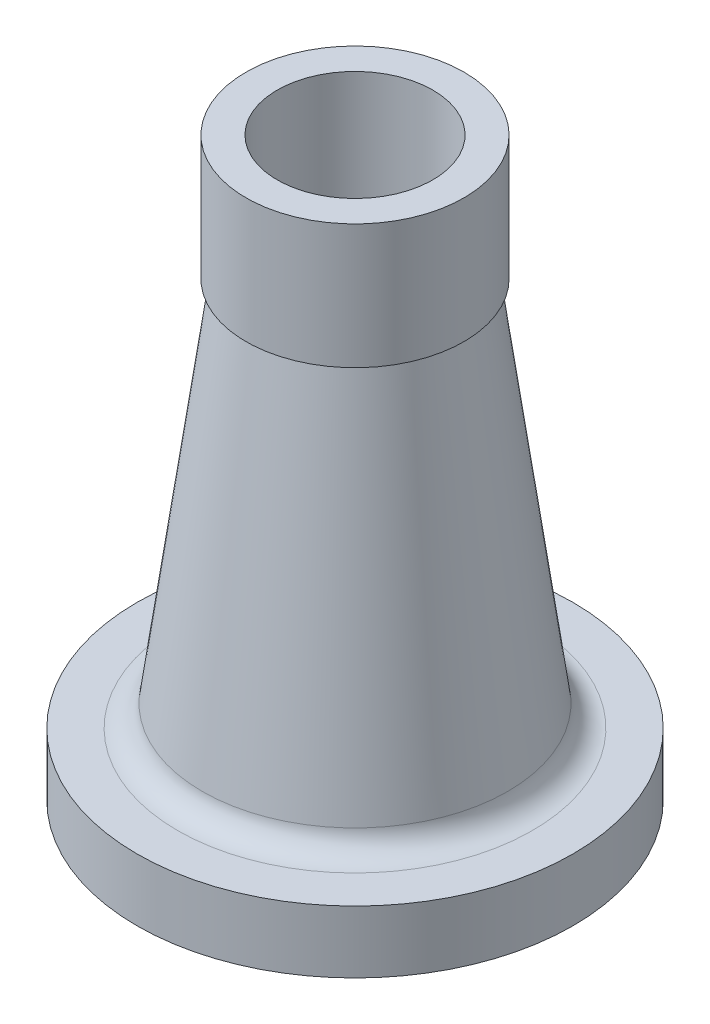
SolidWorks part; units mm, degrees
material "Gray Cast Iron"
ref_plane "Front Plane" through (0, 0, 0) normal (0, 0, 1) x (1, 0, 0)
ref_plane "Top Plane" through (0, 0, 0) normal (0, 1, 0) x (1, 0, 0)
ref_plane "Right Plane" through (0, 0, 0) normal (1, 0, 0) x (0, 0, -1)
sketch "Sketch1" plane through (0, 0, 0) normal (0, 0, 1) x (1, 0, 0)
  line L0 (50, 0) -> (70, 0)
  line L1 (70, 0) -> (70, 20)
  line L2 (70, 20) -> (50, 20)
  line L3 (50, 20) -> (33, 145)
  line L4 (33, 145) -> (35, 145)
  line L5 (35, 145) -> (35, 185)
  line L6 (35, 185) -> (25, 185)
  line L7 (25, 185) -> (25, 129.6172)
  line L8 (25, 129.6172) -> (42.2199, 3)
  line L9 (42.2199, 3) -> (50, 3)
  line L10 (50, 3) -> (50, 0)
  line L11 (0, 0) -> (0, 185) construction
  dimension "D1" = 70
  dimension "D2" = 50
  dimension "D3" = 35
  dimension "D4" = 25
  dimension "D5" = 33
  dimension "D6" = 50
  dimension "D7" = 3
  dimension "D8" = 185
  dimension "D9" = 40
  dimension "D10" = 20
  dimension "D11" = 10
revolve "Revolve1" add sketch "Sketch1" angle 360 about L11
fillet "Fillet1" radius 8 1 edges at (0, 20, -50)
